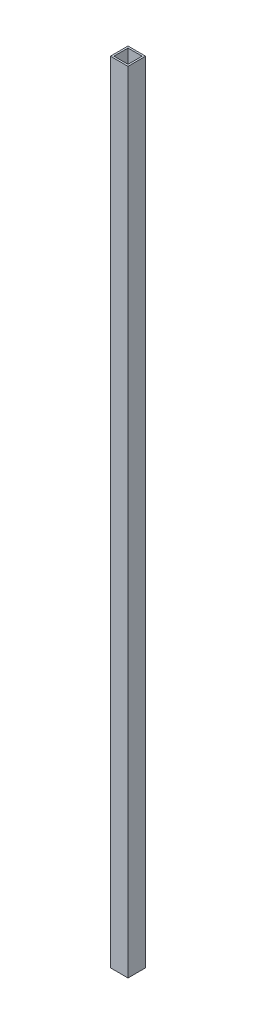
SolidWorks part; units mm, degrees
material "Ti-6Al-4VSolution treated and aged (SS)"
ref_plane "Front Plane" through (0, 0, 0) normal (0, 0, 1) x (1, 0, 0)
ref_plane "Top Plane" through (0, 0, 0) normal (0, 1, 0) x (1, 0, 0)
ref_plane "Right Plane" through (0, 0, 0) normal (1, 0, 0) x (0, 0, -1)
sketch "Sketch1" plane through (0, 0, 0) normal (0, 1, 0) x (1, 0, 0)
  line L14 (0, 0) -> (100, 0)
  line L15 (100, 0) -> (100, 100)
  line L18 (100, 100) -> (0, 100)
  line L20 (0, 100) -> (0, 0)
  dimension "D1" = 100
  dimension "D2" = 100
extrude "Boss-Extrude1" add sketch "Sketch1" against normal blind 4482
sketch "Sketch5" plane through (0, 0, 0) normal (0, 1, 0) x (1, 0, 0)
  line L4 (100, 0) -> (100, 100) construction
  line L5 (10, 10) -> (90, 10)
  line L8 (10, 10) -> (10, 90)
  line L9 (10, 90) -> (90, 90)
  line L10 (90, 10) -> (90, 90)
  line L11 (100, 100) -> (0, 100) construction
  line L12 (0, 100) -> (0, 0) construction
  line L13 (0, 0) -> (100, 0) construction
  dimension "D1" = 10
  dimension "D2" = 10
  dimension "D3" = 10
  dimension "D4" = 10
extrude "Cut-Extrude1" cut sketch "Sketch5" against normal through all
